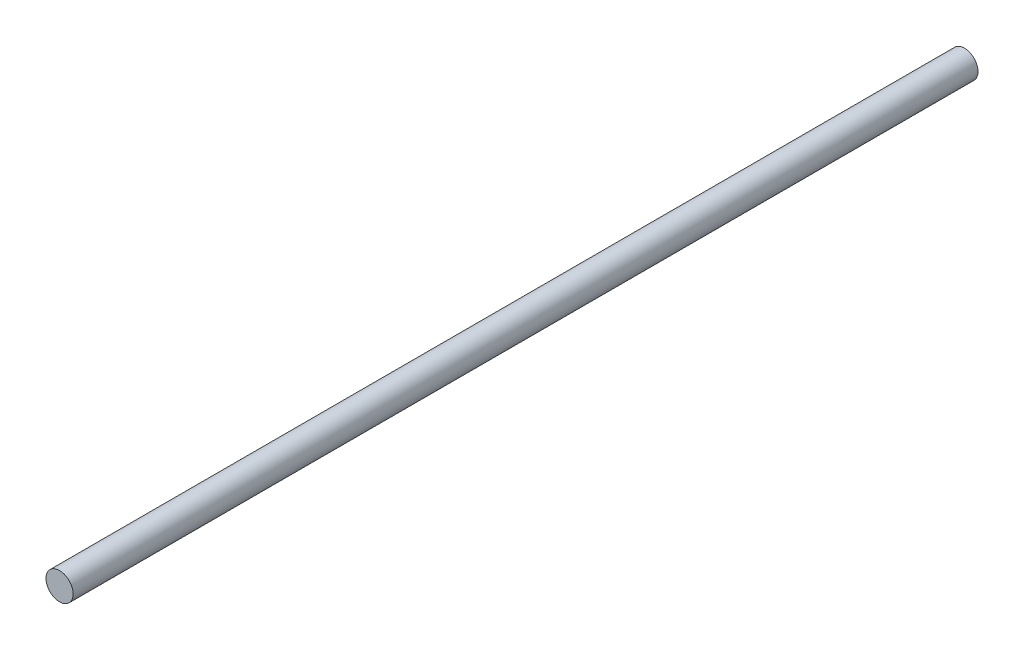
SolidWorks part; units mm, degrees
ref_plane "前视基准面" through (0, 0, 0) normal (0, 0, 1) x (1, 0, 0)
ref_plane "上视基准面" through (0, 0, 0) normal (0, 1, 0) x (1, 0, 0)
ref_plane "右视基准面" through (0, 0, 0) normal (1, 0, 0) x (0, 0, -1)
sketch "草图1" plane through (0, 0, 0) normal (0, 0, 1) x (1, 0, 0)
  circle A0 centre (0, 0) radius 6
  dimension "D1" = 12
extrude "凸台-拉伸1" add sketch "草图1" along normal blind 400
